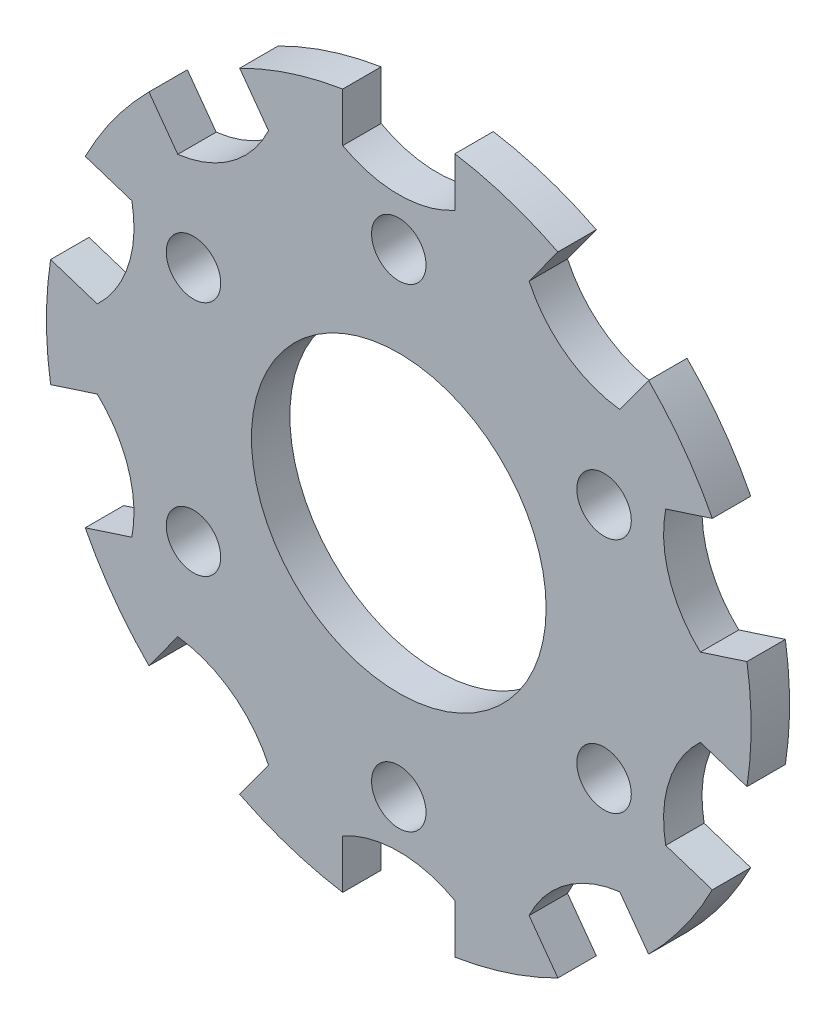
SolidWorks part; units mm, degrees
ref_plane "Front Plane" through (0, 0, 0) normal (0, 0, 1) x (1, 0, 0)
ref_plane "Top Plane" through (0, 0, 0) normal (0, 1, 0) x (1, 0, 0)
ref_plane "Right Plane" through (0, 0, 0) normal (1, 0, 0) x (0, 0, -1)
sketch "Sketch2" plane through (0, 0, 0) normal (0, 0, 1) x (1, 0, 0)
  line L0 (0, 33.0131) -> (0, -39.3254) construction
  line L1 (-57.9788, 0) -> (66.302, 0) construction
  line L2 (-4.375, 27.1498) -> (-4.375, 23.324)
  line L3 (4.375, 27.1498) -> (4.375, 23.324)
  line L4 (19.4977, 19.3931) -> (17.249, 16.298)
  line L5 (12.4188, 24.5362) -> (10.1701, 21.4411)
  line L6 (27.1729, 4.2289) -> (23.5344, 3.0466)
  line L7 (24.469, 12.5506) -> (20.8305, 11.3684)
  line L8 (24.469, -12.5506) -> (20.8305, -11.3684)
  line L9 (27.1729, -4.2289) -> (23.5344, -3.0466)
  line L10 (12.4188, -24.5362) -> (10.1701, -21.4411)
  line L11 (19.4977, -19.3931) -> (17.249, -16.298)
  line L12 (-4.375, -27.1498) -> (-4.375, -23.324)
  line L13 (4.375, -27.1498) -> (4.375, -23.324)
  line L14 (-19.4977, -19.3931) -> (-17.249, -16.298)
  line L15 (-12.4188, -24.5362) -> (-10.1701, -21.4411)
  line L16 (-27.1729, -4.2289) -> (-23.5344, -3.0466)
  line L17 (-24.469, -12.5506) -> (-20.8305, -11.3684)
  line L18 (-24.469, 12.5506) -> (-20.8305, 11.3684)
  line L19 (-27.1729, 4.2289) -> (-23.5344, 3.0466)
  line L20 (-12.4188, 24.5362) -> (-10.1701, 21.4411)
  line L21 (-19.4977, 19.3931) -> (-17.249, 16.298)
  circle A0 centre (0, 0) radius 27.5
  circle A1 centre (0, 0) radius 18.5
  circle A2 centre (0, 0) radius 19.75 construction
  circle A3 centre (-16.0215, 9.25) radius 2.125
  circle A4 centre (0, 18.5) radius 2.125
  circle A5 centre (16.0215, 9.25) radius 2.125
  circle A6 centre (16.0215, -9.25) radius 2.125
  circle A7 centre (0, -18.5) radius 2.125
  circle A8 centre (-16.0215, -9.25) radius 2.125
  arc A9 (-4.375, 23.324) -> (4.375, 23.324) centre (0, 31.2162) ccw
  arc A10 (10.1701, 21.4411) -> (17.249, 16.298) centre (18.3484, 25.2544) ccw
  arc A11 (20.8305, 11.3684) -> (23.5344, 3.0466) centre (29.6883, 9.6463) ccw
  arc A12 (23.5344, -3.0466) -> (20.8305, -11.3684) centre (29.6883, -9.6463) ccw
  arc A13 (17.249, -16.298) -> (10.1701, -21.4411) centre (18.3484, -25.2544) ccw
  arc A14 (4.375, -23.324) -> (-4.375, -23.324) centre (0, -31.2162) ccw
  arc A15 (-10.1701, -21.4411) -> (-17.249, -16.298) centre (-18.3484, -25.2544) ccw
  arc A16 (-20.8305, -11.3684) -> (-23.5344, -3.0466) centre (-29.6883, -9.6463) ccw
  arc A17 (-23.5344, 3.0466) -> (-20.8305, 11.3684) centre (-29.6883, 9.6463) ccw
  arc A18 (-17.249, 16.298) -> (-10.1701, 21.4411) centre (-18.3484, 25.2544) ccw
  circle A19 centre (0, 0) radius 11.5
  point P25 (0, 0)
  point P75 (0, 0)
  dimension "D1" = 55
  dimension "37" = 37
  dimension "D3" = 39.5
  dimension "D4" = 4.25
  dimension "D8" = 23
  dimension "D6" = 10
  dimension "D7" = 8.75
  dimension "D5" = 6
extrude "Boss-Extrude2" add sketch "Sketch2" along normal blind 3 contours A18 L21 A0 L18 A17 L19 L16 A16 L17 L14 A15 L15 L12 A14 L13 L10 A13 L11 L8 A12 L9 L6 A11 L7 L4 A10 L5 L3 A9 L2 L20 A8 A1 A3 A4 A5 A6 | A8 A1 A7 A6 A5 A4 A3 A19
